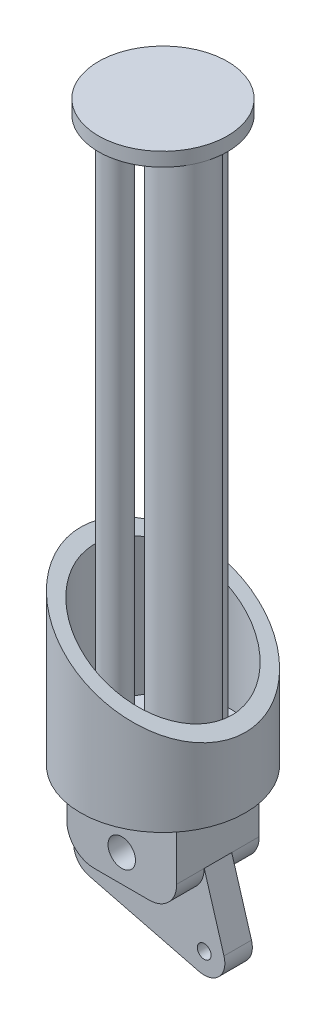
SolidWorks part; units mm, degrees
material "Titanio Ti-8Al-1Mo-1V"
ref_plane "Alzado" through (0, 0, 0) normal (0, 0, 1) x (1, 0, 0)
ref_plane "Planta" through (0, 0, 0) normal (0, 1, 0) x (1, 0, 0)
ref_plane "Vista lateral" through (0, 0, 0) normal (1, 0, 0) x (0, 0, -1)
other "Centro de masa"
sketch "Croquis2" plane through (0, 0, 0) normal (0, 1, 0) x (1, 0, 0)
  circle A0 centre (0, 0) radius 30
  dimension "D1" = 60
extrude "Saliente-Extruir1" add sketch "Croquis2" along normal blind 60
sketch "Croquis3" plane through (0, 0, 0) normal (0, -1, 0) x (1, 0, 0)
  line L1 (20, -15) -> (-20, -15)
  line L2 (20, -15) -> (20, 15)
  line L3 (20, 15) -> (-20, 15)
  line L4 (-20, -15) -> (-20, 15)
  line L5 (20, -15) -> (-20, 15) construction
  line L6 (20, 15) -> (-20, -15) construction
  point P0 (0, 0)
  dimension "D1" = 30
  dimension "D2" = 40
extrude "Saliente-Extruir2" add sketch "Croquis3" along normal blind 30
fillet "Redondeo1" radius 10 2 edges at (-20, -30, 0) (20, -30, 0)
sketch "Croquis4" plane through (0, 0, 15) normal (0, 0, 1) x (1, 0, 0)
  line L0 (0, -30) -> (0, -20) construction
  line L1 (10, -30) -> (-10, -30) construction
  circle A0 centre (0, -20) radius 5
  dimension "D1" = 10
  dimension "D2" = 10
extrude "Cortar-Extruir1" cut sketch "Croquis4" against normal through all contours A0
sketch "Croquis5" plane through (0, 0, 0) normal (0, 0, 1) x (1, 0, 0)
  line L3 (30, 60) -> (-30, 60)
  line L4 (-30, 60) -> (30, 25.359)
  line L5 (30, 0) -> (30, 60) construction
  line L6 (30, 25.359) -> (30, 60)
  dimension "D1" = 30
extrude "Cortar-Extruir2" cut sketch "Croquis5" against normal through all both and the other way through all
ref_plane "Plano1" through (0, 5, 0) normal (0, -1, 0) x (-1, 0, 0)
sketch "Croquis7" plane through (0, 5, 0) normal (0, -1, 0) x (-1, 0, 0)
  circle A0 centre (0, 0) radius 25
extrude "Cortar-Extruir3" cut sketch "Croquis7" against normal through all
sketch "Croquis8" plane through (0, 5, 0) normal (0, 1, 0) x (1, 0, 0)
  line L0 (-12.5, -5) -> (12.5, -5) construction
  line L1 (12.5, -5) -> (0, 16.6506) construction
  line L2 (0, 16.6506) -> (-12.5, -5) construction
  line L3 (0, 0) -> (0, -5) construction
  circle A0 centre (0, 16.6506) radius 5
  circle A1 centre (12.5, -5) radius 10
  circle A2 centre (-12.5, -5) radius 5
  dimension "D1" = 10
  dimension "D2" = 10
  dimension "D5" = 20
  dimension "D3" = 5
  dimension "D4" = 25
extrude "Saliente-Extruir3" add sketch "Croquis8" along normal blind 200
sketch "Croquis10" plane through (0, 205, 0) normal (0, 1, 0) x (1, 0, 0)
  circle A0 centre (0, 0) radius 23.4629
  circle A1 centre (12.5, -5) radius 10 construction
extrude "Saliente-Extruir4" add sketch "Croquis10" along normal blind 5 contours A0
ref_plane "Plano2" through (0, 0, 0) normal (0, 0, -1) x (-1, 0, 0)
sketch "Croquis11" plane through (0, 0, 0) normal (0, 0, -1) x (-1, 0, 0)
  line L0 (-20, -46.1569) -> (-20, -20) construction
  line L1 (20, -36.0649) -> (20, -18.6546) construction
  line L2 (20, -20) -> (20, 0) construction
  line L3 (-27.1851, -44.0064) -> (-20, -20)
  line L4 (-18.1653, -53.429) -> (21.8347, -43.3371)
  line L5 (26.7684, -32.8341) -> (20, -18.6546)
  line L6 (20, -18.6546) -> (0.4525, -27.9897)
  line L7 (0.4525, -27.9897) -> (-20, -20)
  circle A0 centre (-20, -46.1569) radius 2.5
  circle A1 centre (20, -36.0649) radius 2.5
  arc A2 (21.8347, -43.3371) -> (26.7684, -32.8341) centre (20, -36.0649) ccw
  arc A3 (-27.1851, -44.0064) -> (-18.1653, -53.429) centre (-20, -46.1569) ccw
  dimension "D1" = 5
  dimension "D2" = 15
  dimension "D3" = 15
extrude "Saliente-Extruir5" add sketch "Croquis11" along normal mid plane 10 contours L3 A3 L4 A2 L5 L6 L7 A0 A1
